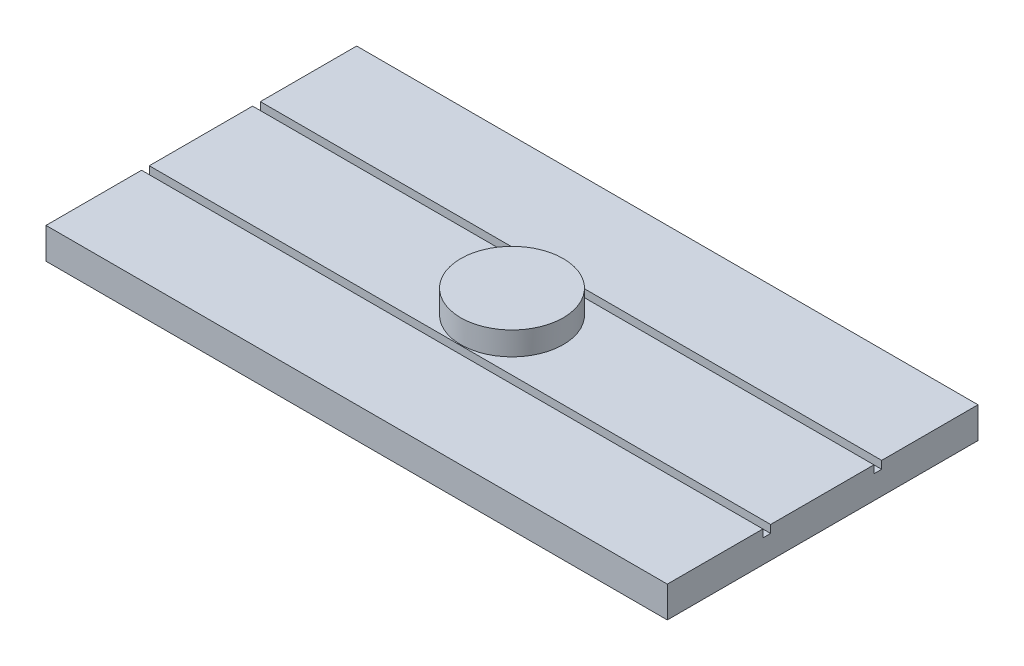
SolidWorks part; units mm, degrees
ref_plane "Front Plane" through (0, 0, 0) normal (0, 0, 1) x (1, 0, 0)
ref_plane "Top Plane" through (0, 0, 0) normal (0, 1, 0) x (1, 0, 0)
ref_plane "Right Plane" through (0, 0, 0) normal (1, 0, 0) x (0, 0, -1)
sketch "Sketch1" plane through (0, 0, 0) normal (0, 1, 0) x (1, 0, 0)
  line L1 (0, 0) -> (101.6, 0)
  line L2 (0, 0) -> (0, 50.8)
  line L3 (0, 50.8) -> (101.6, 50.8)
  line L4 (101.6, 0) -> (101.6, 50.8)
  dimension "D1" = 101.6
  dimension "D2" = 50.8
extrude "Boss-Extrude1" add sketch "Sketch1" along normal blind 5.08
sketch "Sketch2" plane through (0, 0, 0) normal (0, 1, 0) x (1, 0, 0)
  circle A0 centre (50.8, 25.4) radius 8.382
extrude "Boss-Extrude2" add sketch "Sketch2" along normal blind 8.89
sketch "Sketch4" plane through (0, 5.08, 0) normal (0, 1, 0) x (1, 0, 0)
  line L3 (0, 50.8) -> (0, 0) construction
  line L4 (0, 33.782) -> (101.6, 33.782)
  line L5 (0, 33.782) -> (0, 35.052)
  line L6 (0, 35.052) -> (101.6, 35.052)
  line L8 (101.6, 33.782) -> (101.6, 35.052)
  line L9 (101.6, 0) -> (101.6, 50.8) construction
extrude "Cut-Extrude1" cut sketch "Sketch4" against normal blind 1.27 contours L6 L8 L4 L5
sketch "Sketch5" plane through (0, 5.08, 0) normal (0, 1, 0) x (1, 0, 0)
  line L0 (0, 33.782) -> (0, 0) construction
  line L1 (0, 16.891) -> (101.6, 16.891)
  line L2 (0, 16.891) -> (0, 15.621)
  line L3 (0, 15.621) -> (101.6, 15.621)
  line L4 (101.6, 16.891) -> (101.6, 15.621)
  line L5 (101.6, 0) -> (101.6, 33.782) construction
extrude "Cut-Extrude2" cut sketch "Sketch5" against normal blind 1.27
